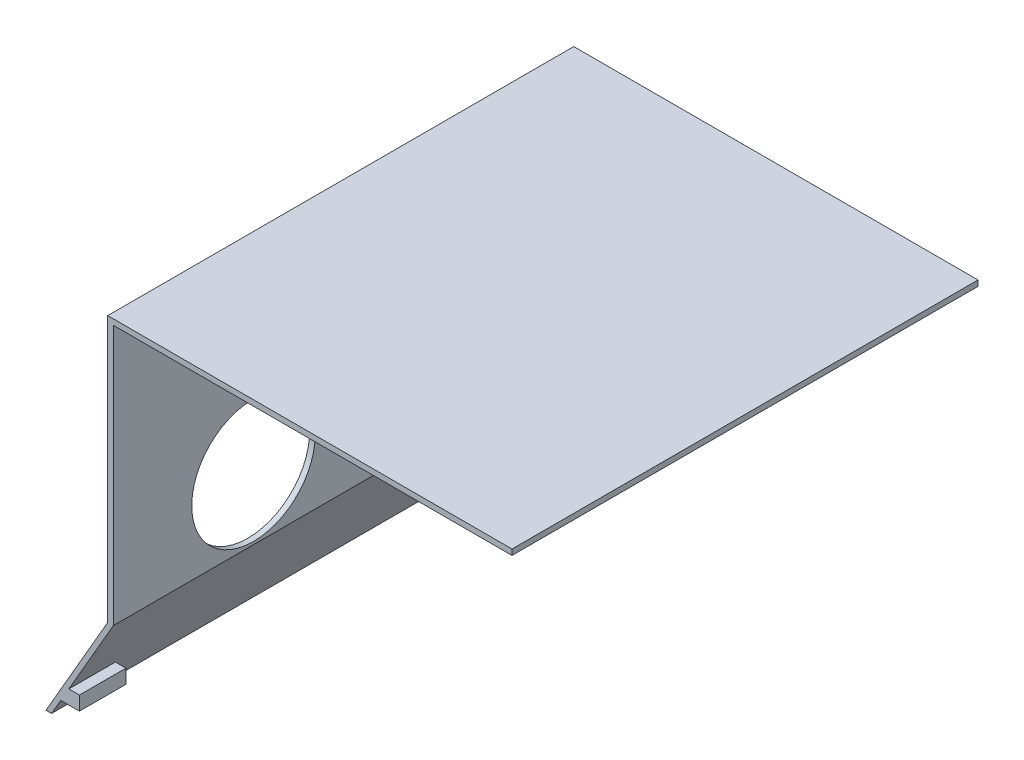
SolidWorks part; units mm, degrees
ref_plane "Alzado" through (0, 0, 0) normal (0, 0, 1) x (1, 0, 0)
ref_plane "Planta" through (0, 0, 0) normal (0, 1, 0) x (1, 0, 0)
ref_plane "Vista lateral" through (0, 0, 0) normal (1, 0, 0) x (0, 0, -1)
sketch "Croquis1" plane through (0, 0, 0) normal (0, 0, 1) x (1, 0, 0)
  line L0 (0, 0) -> (1.2, 0)
  line L1 (1.2, 0) -> (14.45, 22.9497)
  line L5 (13.25, 22.9497) -> (0, 0)
  line L6 (14.45, 22.9497) -> (14.45, 78.7597)
  line L7 (14.45, 78.7597) -> (100, 78.7597)
  line L8 (100, 78.7597) -> (100, 79.9597)
  line L9 (100, 79.9597) -> (13.25, 79.9597)
  line L10 (13.25, 79.9597) -> (13.25, 22.9497)
  line L11 (1.2, 0) -> (20.9215, 0) construction
  line L14 (3.398, 3.8071) -> (7.398, 3.8071)
  line L15 (7.398, 3.8071) -> (7.398, 6.8071)
  line L16 (7.398, 6.8071) -> (5.1301, 6.8071)
  dimension "D1" = 1.2
  dimension "D2" = 60
  dimension "D3" = 26.5
  dimension "D4" = 1.2
  dimension "D5" = 85.55
  dimension "D6" = 55.81
  dimension "D7" = 3
  dimension "D8" = 4
extrude "Saliente-Extruir1" add sketch "Croquis1" against normal blind 100 contours L10 L5 L0 L1 L6 L7 L8 L9
sketch "Croquis2" plane through (0, 0, 0) normal (0, 0, 1) x (1, 0, 0)
  line L0 (1.2, 0) -> (6.4649, 0) construction
  line L1 (3.163, 3.4) -> (3.163, 0) construction
  line L2 (1.2, 0) -> (14.45, 22.9497) construction
  line L3 (3.163, 3.4) -> (7.163, 3.4)
  line L4 (7.163, 3.4) -> (7.163, 6.4)
  line L5 (7.163, 6.4) -> (4.895, 6.4)
  line L6 (4.895, 6.4) -> (3.163, 3.4)
  dimension "D1" = 4
  dimension "D2" = 3
extrude "Saliente-Extruir2" add sketch "Croquis2" against normal blind 10
sketch "Croquis4" plane through (0, 0, -100) normal (0, 0, -1) x (-1, 0, 0)
  line L0 (-3.163, 3.4) -> (-7.163, 3.4)
  line L1 (-7.163, 3.4) -> (-7.163, 6.4)
  line L2 (-7.163, 6.4) -> (-4.895, 6.4)
  line L3 (-4.895, 6.4) -> (-3.163, 3.4)
extrude "Saliente-Extruir3" add sketch "Croquis4" against normal blind 10
sketch "Croquis9" plane through (13.25, 0, 0) normal (-1, 0, 0) x (0, 0, 1)
  line L0 (-100, 0) -> (-69.6, 0)
  line L1 (-100, 0) -> (0, 0) construction
  line L2 (-69.6, 0) -> (-69.6, 36.8)
  line L3 (-69.6, 36.8) -> (-30.07, 36.8)
  circle A0 centre (-69.6, 36.8) radius 13.25
  circle A1 centre (-30.07, 36.8) radius 13.25
  dimension "D2" = 26.5
  dimension "D1" = 30.4
  dimension "D3" = 36.8
  dimension "D4" = 39.53
extrude "Cortar-Extruir5" cut sketch "Croquis9" against normal blind 10 contours L3 A0 L2 | L2 A0 L3 | A1
